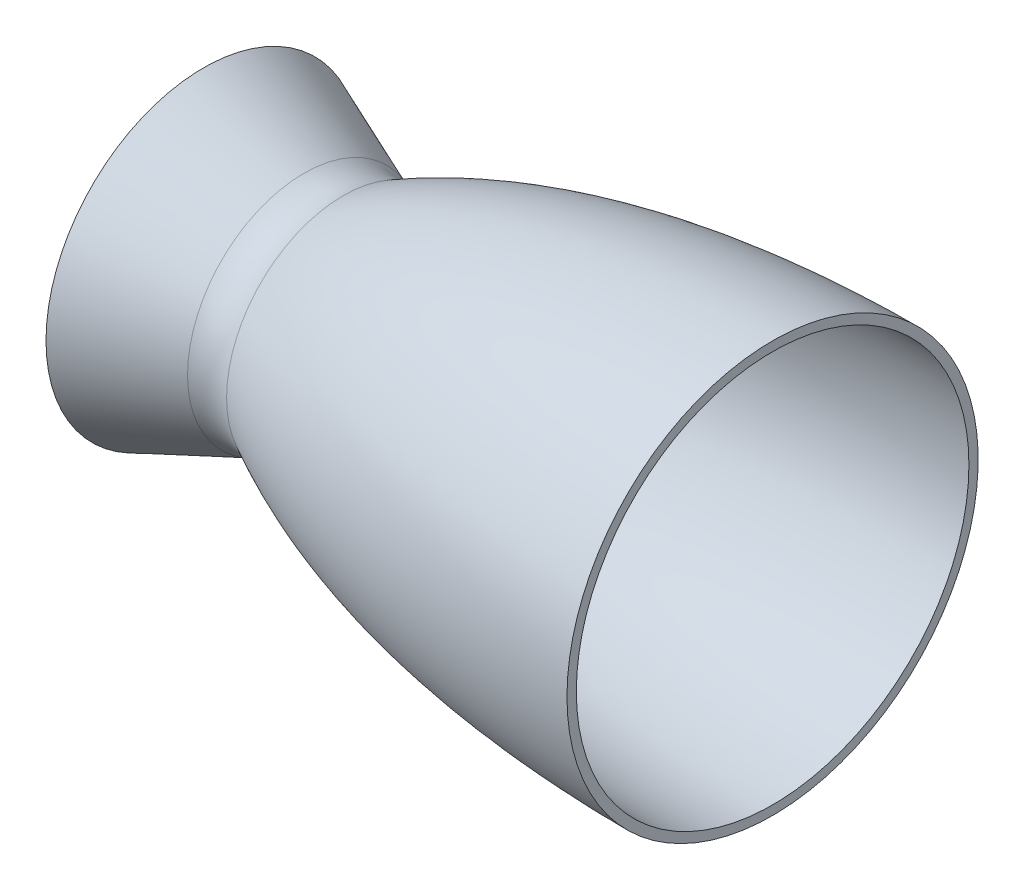
SolidWorks part; units mm, degrees
ref_plane "Front Plane" through (0, 0, 0) normal (0, 0, 1) x (1, 0, 0)
ref_plane "Top Plane" through (0, 0, 0) normal (0, 1, 0) x (1, 0, 0)
ref_plane "Right Plane" through (0, 0, 0) normal (1, 0, 0) x (0, 0, -1)
curve "Curve1"
  spline degree 3 poles (0, 35, 0) (0.555, 35.2921, 0) (1.5295, 35.805, 0) (2.9372, 36.5286, 0) (4.2269, 37.1794, 0) (5.542, 37.8302, 0) (6.8834, 38.481, 0) (8.2519, 39.1316, 0) (9.6485, 39.782, 0) (11.0741, 40.4321, 0) (12.5297, 41.0818, 0) (14.0164, 41.7309, 0) (15.5351, 42.3793, 0) (17.0871, 43.0268, 0) (18.6734, 43.6732, 0) (20.2952, 44.3184, 0) (21.9539, 44.9621, 0) (23.6506, 45.6042, 0) (25.3866, 46.2442, 0) (27.1635, 46.8821, 0) (28.9826, 47.5175, 0) (30.8454, 48.1501, 0) (32.7535, 48.7795, 0) (34.7085, 49.4055, 0) (36.7122, 50.0275, 0) (38.7661, 50.6453, 0) (40.8724, 51.2584, 0) (43.0327, 51.8662, 0) (45.2492, 52.4683, 0) (47.5239, 53.0642, 0) (49.8591, 53.6532, 0) (52.257, 54.2348, 0) (54.72, 54.8083, 0) (57.2506, 55.373, 0) (59.8514, 55.9281, 0) (62.5252, 56.4728, 0) (65.2749, 57.0063, 0) (68.1035, 57.5277, 0) (71.0142, 58.0359, 0) (74.0102, 58.53, 0) (77.0952, 59.0088, 0) (80.2727, 59.4712, 0) (83.5467, 59.9158, 0) (86.9213, 60.3413, 0) (90.4007, 60.7463, 0) (93.9895, 61.1292, 0) (97.6926, 61.4883, 0) (101.5149, 61.8219, 0) (105.4618, 62.1281, 0) (109.5391, 62.4048, 0) (113.7526, 62.65, 0) (118.1088, 62.861, 0) (122.6145, 63.0358, 0) (127.2768, 63.1706, 0) (132.1033, 63.2666, 0) (135.3767, 63.2916, 0) (137.042, 63.3043, 0) knots 0 0 0 0 0.013316 0.023384 0.033606 0.04399 0.05454 0.065263 0.076165 0.087252 0.098532 0.110011 0.121696 0.133595 0.145716 0.158067 0.170657 0.183493 0.196586 0.209945 0.223579 0.237499 0.251716 0.266241 0.281086 0.296262 0.311783 0.327663 0.343914 0.360552 0.377592 0.395049 0.412942 0.431287 0.450103 0.469409 0.489227 0.509576 0.53048 0.551963 0.57405 0.596767 0.620142 0.644205 0.668987 0.694519 0.720839 0.747982 0.775987 0.804896 0.834753 0.865604 0.8975 0.930493 0.96464 1 1 1 1
sketch "Sketch1" plane through (0, 0, 0) normal (0, 0, 1) x (1, 0, 0)
  line L0 (-14.0754, 37.5683) -> (-46.471, 50.817)
  line L1 (-15.211, 34.7915) -> (-47.6066, 48.0402)
  line L2 (-46.471, 50.817) -> (-47.6066, 48.0402)
  line L4 (-87.9328, 0) -> (164.2442, 0) construction
  line L6 (137.0191, 66.3042) -> (137.042, 63.3043)
  arc A1 (-14.0754, 37.5683) -> (-1.3972, 37.6548) centre (-7.8291, 51.2058) ccw
  arc A2 (-15.211, 34.7915) -> (0, 35) centre (-7.8291, 51.2058) ccw
  spline S1 degree 3 poles (-1059.7891, 1728.5502) (-81.1049, -34.6445) (-45.0455, 11.8603) (2.9372, 36.5286) (4.6705, 37.4032) (6.4418, 38.271) (8.7235, 39.3558) (10.6053, 40.2229) (13.0323, 41.3061) (15.0362, 42.1711) (17.0871, 43.0268) (18.6734, 43.6732) (20.857, 44.5419) (23.0943, 45.399) (25.9891, 46.4664) (28.3869, 47.3152) (30.8454, 48.1501) (32.7535, 48.7795) (34.7085, 49.4055) (36.7122, 50.0275) (39.4823, 50.8607) (42.3273, 51.6746) (45.2492, 52.4683) (47.5239, 53.0642) (50.6762, 53.8593) (53.9175, 54.6292) (57.2506, 55.373) (59.8514, 55.9281) (62.5252, 56.4728) (65.2749, 57.0063) (69.0985, 57.7111) (74.0922, 58.5579) (79.242, 59.3312) (83.5467, 59.9158) (88.1144, 60.4917) (92.8279, 61.0165) (97.6926, 61.4883) (101.5149, 61.8219) (105.4618, 62.1281) (109.5391, 62.4048) (113.7526, 62.65) (118.1088, 62.861) (122.6145, 63.0358) (127.2768, 63.1706) (227.8243, 65.17) (327.2764, 30.4279) (399.6265, 2038.6906) knots -1.111965 -1.111965 -1.111965 -1.111965 0.013316 0.023384 0.033606 0.05454 0.065263 0.087252 0.098532 0.121696 0.133595 0.145716 0.158067 0.183493 0.196586 0.223579 0.237499 0.251716 0.266241 0.281086 0.296262 0.327663 0.343914 0.360552 0.377592 0.412942 0.431287 0.450103 0.469409 0.489227 0.509576 0.551963 0.596767 0.620142 0.644205 0.694519 0.720839 0.747982 0.775987 0.804896 0.834753 0.865604 0.8975 0.930493 0.96464 3.032824 3.032824 3.032824 3.032824 only from (0, 35) to (137.042, 63.3043) construction
  spline S2 degree 3 poles (1145.1504, 2809.2889) (-68.2962, -28.5285) (-47.551, 13.8072) (1.2433, 39.0319) (1.9092, 39.371) (3.9138, 40.3772) (5.258, 41.0322) (9.3115, 42.9499) (12.0422, 44.1656) (20.3059, 47.6314) (25.9103, 49.6997) (37.249, 53.3987) (42.9837, 55.0299) (54.5381, 57.9059) (60.358, 59.1509) (72.0508, 61.3031) (77.9238, 62.2104) (89.7002, 63.7299) (95.6037, 64.3422) (107.4254, 65.3092) (113.3437, 65.6637) (122.2242, 66.0261) (125.1842, 66.118) (129.6251, 66.218) (131.1081, 66.2447) (244.2888, 67.6588) (328.8055, 27.7497) (347.5579, 3050.1997) knots -1.115523 -1.115523 -1.115523 -1.115523 0.015625 0.015625 0.03125 0.03125 0.0625 0.0625 0.125 0.125 0.25 0.25 0.375 0.375 0.5 0.5 0.625 0.625 0.75 0.75 0.875 0.875 0.9375 0.9375 0.96875 0.96875 3.325087 3.325087 3.325087 3.325087 only from (-1.3972, 37.6548) to (137.0191, 66.3042)
  spline S3 degree 3 poles (-1.3972, 37.6548) (-0.746, 37.9975) (-0.0864, 38.3445) (1.2433, 39.0319) (1.9092, 39.371) (3.9138, 40.3772) (5.258, 41.0322) (9.3115, 42.9499) (12.0422, 44.1656) (20.3059, 47.6314) (25.9103, 49.6997) (37.249, 53.3987) (42.9837, 55.0299) (54.5381, 57.9059) (60.358, 59.1509) (72.0508, 61.3031) (77.9238, 62.2104) (89.7002, 63.7299) (95.6037, 64.3422) (107.4254, 65.3092) (113.3437, 65.6637) (122.2242, 66.0261) (125.1842, 66.118) (129.6251, 66.218) (131.1081, 66.2447) (134.0708, 66.2817) (135.5474, 66.2929) (137.0191, 66.3042) knots 0 0 0 0 0.015625 0.015625 0.03125 0.03125 0.0625 0.0625 0.125 0.125 0.25 0.25 0.375 0.375 0.5 0.5 0.625 0.625 0.75 0.75 0.875 0.875 0.9375 0.9375 0.96875 0.96875 1 1 1 1
  spline S4 degree 3 poles (0, 35) (0.555, 35.2921) (1.5295, 35.805) (2.9372, 36.5286) (4.6705, 37.4032) (6.4418, 38.271) (8.7235, 39.3558) (10.6053, 40.2229) (13.0323, 41.3061) (15.0362, 42.1711) (17.0871, 43.0268) (18.6734, 43.6732) (20.857, 44.5419) (23.0943, 45.399) (25.9891, 46.4664) (28.3869, 47.3152) (30.8454, 48.1501) (32.7535, 48.7795) (34.7085, 49.4055) (36.7122, 50.0275) (39.4823, 50.8607) (42.3273, 51.6746) (45.2492, 52.4683) (47.5239, 53.0642) (50.6762, 53.8593) (53.9175, 54.6292) (57.2506, 55.373) (59.8514, 55.9281) (62.5252, 56.4728) (65.2749, 57.0063) (69.0985, 57.7111) (74.0922, 58.5579) (79.242, 59.3312) (83.5467, 59.9158) (88.1144, 60.4917) (92.8279, 61.0165) (97.6926, 61.4883) (101.5149, 61.8219) (105.4618, 62.1281) (109.5391, 62.4048) (113.7526, 62.65) (118.1088, 62.861) (122.6145, 63.0358) (127.2768, 63.1706) (132.1033, 63.2666) (135.3767, 63.2916) (137.042, 63.3043) knots 0 0 0 0 0.013316 0.023384 0.033606 0.05454 0.065263 0.087252 0.098532 0.121696 0.133595 0.145716 0.158067 0.183493 0.196586 0.223579 0.237499 0.251716 0.266241 0.281086 0.296262 0.327663 0.343914 0.360552 0.377592 0.412942 0.431287 0.450103 0.469409 0.489227 0.509576 0.551963 0.596767 0.620142 0.644205 0.694519 0.720839 0.747982 0.775987 0.804896 0.834753 0.865604 0.8975 0.930493 0.96464 1 1 1 1
  dimension "D4" = 15
  dimension "D3" = 35
  dimension "D1" = 3
  dimension "D2" = 3
revolve "Revolve1" add sketch "Sketch1" angle 360 about L4
